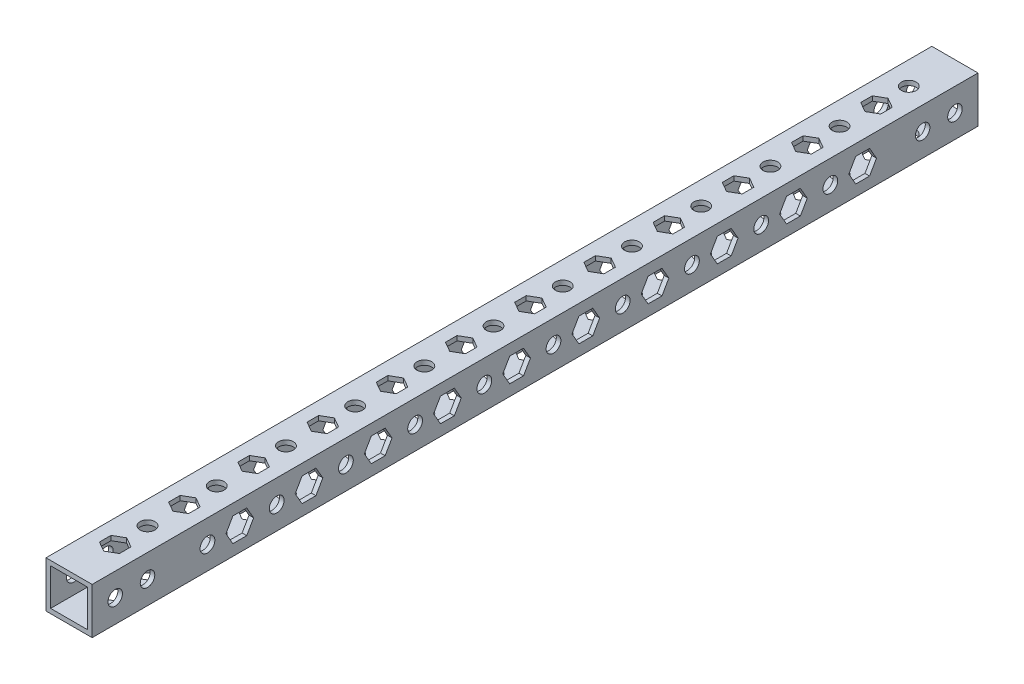
SolidWorks part; units mm, degrees
ref_plane "前视基准面" through (0, 0, 0) normal (0, 0, 1) x (1, 0, 0)
ref_plane "上视基准面" through (0, 0, 0) normal (0, 1, 0) x (1, 0, 0)
ref_plane "右视基准面" through (0, 0, 0) normal (1, 0, 0) x (0, 0, -1)
other "Configuration Table"
sketch "草图1" plane through (0, 0, 0) normal (0, 0, 1) x (1, 0, 0)
  line L1 (0, 0) -> (10, 0)
  line L2 (0, 0) -> (0, -10)
  line L3 (0, -10) -> (10, -10)
  line L4 (10, 0) -> (10, -10)
  dimension "D1" = 10
  dimension "D2" = 10
extrude "拉伸-薄壁1" add sketch "草图1" along normal blind 192 thin
sketch "草图2" plane through (10, 0, 0) normal (1, 0, 0) x (0, 0, -1)
  line L0 (-96, 0) -> (-96, -10) construction
  line L1 (-192, 0) -> (0, 0) construction
  line L2 (-192, -10) -> (0, -10) construction
  line L3 (0, -5) -> (-192, -5) construction
  line L4 (0, -10) -> (0, 0) construction
  line L5 (-192, -10) -> (-192, 0) construction
  line L6 (-143.5, -2.4019) -> (-146.5, -2.4019)
  line L7 (-157, -5) -> (-158.5, -2.4019)
  line L8 (-158.5, -2.4019) -> (-161.5, -2.4019)
  line L9 (-161.5, -2.4019) -> (-163, -5)
  line L10 (-163, -5) -> (-161.5, -7.5981)
  line L11 (-161.5, -7.5981) -> (-158.5, -7.5981)
  line L12 (-158.5, -7.5981) -> (-157, -5)
  line L13 (-142, -5) -> (-143.5, -2.4019)
  line L14 (-143.5, -7.5981) -> (-142, -5)
  line L15 (-146.5, -7.5981) -> (-143.5, -7.5981)
  line L16 (-148, -5) -> (-146.5, -7.5981)
  line L17 (-146.5, -2.4019) -> (-148, -5)
  line L18 (-128.5, -2.4019) -> (-131.5, -2.4019)
  line L19 (-127, -5) -> (-128.5, -2.4019)
  line L20 (-128.5, -7.5981) -> (-127, -5)
  line L21 (-131.5, -7.5981) -> (-128.5, -7.5981)
  line L22 (-133, -5) -> (-131.5, -7.5981)
  line L23 (-131.5, -2.4019) -> (-133, -5)
  line L24 (-113.5, -2.4019) -> (-116.5, -2.4019)
  line L25 (-112, -5) -> (-113.5, -2.4019)
  line L26 (-113.5, -7.5981) -> (-112, -5)
  line L27 (-116.5, -7.5981) -> (-113.5, -7.5981)
  line L28 (-118, -5) -> (-116.5, -7.5981)
  line L29 (-116.5, -2.4019) -> (-118, -5)
  line L30 (-98.5, -2.4019) -> (-101.5, -2.4019)
  line L31 (-97, -5) -> (-98.5, -2.4019)
  line L32 (-98.5, -7.5981) -> (-97, -5)
  line L33 (-101.5, -7.5981) -> (-98.5, -7.5981)
  line L34 (-103, -5) -> (-101.5, -7.5981)
  line L35 (-101.5, -2.4019) -> (-103, -5)
  line L36 (-83.5, -2.4019) -> (-86.5, -2.4019)
  line L37 (-82, -5) -> (-83.5, -2.4019)
  line L38 (-83.5, -7.5981) -> (-82, -5)
  line L39 (-86.5, -7.5981) -> (-83.5, -7.5981)
  line L40 (-88, -5) -> (-86.5, -7.5981)
  line L41 (-86.5, -2.4019) -> (-88, -5)
  line L42 (-68.5, -2.4019) -> (-71.5, -2.4019)
  line L43 (-67, -5) -> (-68.5, -2.4019)
  line L44 (-68.5, -7.5981) -> (-67, -5)
  line L45 (-71.5, -7.5981) -> (-68.5, -7.5981)
  line L46 (-73, -5) -> (-71.5, -7.5981)
  line L47 (-71.5, -2.4019) -> (-73, -5)
  line L48 (-53.5, -2.4019) -> (-56.5, -2.4019)
  line L49 (-52, -5) -> (-53.5, -2.4019)
  line L50 (-53.5, -7.5981) -> (-52, -5)
  line L51 (-56.5, -7.5981) -> (-53.5, -7.5981)
  line L52 (-58, -5) -> (-56.5, -7.5981)
  line L53 (-56.5, -2.4019) -> (-58, -5)
  line L54 (-38.5, -2.4019) -> (-41.5, -2.4019)
  line L55 (-37, -5) -> (-38.5, -2.4019)
  line L56 (-38.5, -7.5981) -> (-37, -5)
  line L57 (-41.5, -7.5981) -> (-38.5, -7.5981)
  line L58 (-43, -5) -> (-41.5, -7.5981)
  line L59 (-41.5, -2.4019) -> (-43, -5)
  line L60 (-23.5, -2.4019) -> (-26.5, -2.4019)
  line L61 (-22, -5) -> (-23.5, -2.4019)
  line L62 (-23.5, -7.5981) -> (-22, -5)
  line L63 (-26.5, -7.5981) -> (-23.5, -7.5981)
  line L64 (-28, -5) -> (-26.5, -7.5981)
  line L65 (-26.5, -2.4019) -> (-28, -5)
  circle A0 centre (-5, -5) radius 1.575
  circle A1 centre (-187, -5) radius 1.575
  circle A2 centre (-12, -5) radius 1.575
  circle A3 centre (-180, -5) radius 1.575
  circle A4 centre (-167, -5) radius 1.6
  circle A5 centre (-160, -5) radius 2.5981 construction
  circle A6 centre (-152, -5) radius 1.6
  circle A7 centre (-145, -5) radius 2.5981 construction
  circle A8 centre (-137, -5) radius 1.6
  circle A9 centre (-130, -5) radius 2.5981 construction
  circle A10 centre (-122, -5) radius 1.6
  circle A11 centre (-115, -5) radius 2.5981 construction
  circle A12 centre (-107, -5) radius 1.6
  circle A13 centre (-100, -5) radius 2.5981 construction
  circle A14 centre (-92, -5) radius 1.6
  circle A15 centre (-85, -5) radius 2.5981 construction
  circle A16 centre (-77, -5) radius 1.6
  circle A17 centre (-70, -5) radius 2.5981 construction
  circle A18 centre (-62, -5) radius 1.6
  circle A19 centre (-55, -5) radius 2.5981 construction
  circle A20 centre (-47, -5) radius 1.6
  circle A21 centre (-40, -5) radius 2.5981 construction
  circle A22 centre (-32, -5) radius 1.6
  circle A23 centre (-25, -5) radius 2.5981 construction
  dimension "D1" = 3.15
  dimension "D3" = 3.15
  dimension "D5" = 3.2
  dimension "D2" = 91
  dimension "D4" = 7
  dimension "D6" = 3
  dimension "D7" = 7
  dimension "D8" = 25
  dimension "D9" = 15
extrude "切除-拉伸1" cut sketch "草图2" against normal through all
sketch "草图3" plane through (0, 0, 0) normal (0, 1, 0) x (1, 0, 0)
  line L0 (5, 0) -> (5, -192) construction
  line L1 (10, 0) -> (0, 0) construction
  line L2 (10, -192) -> (0, -192) construction
  line L3 (7.1651, -30.75) -> (5, -29.5)
  line L4 (5, -14.5) -> (2.8349, -15.75)
  line L5 (2.8349, -15.75) -> (2.8349, -18.25)
  line L6 (2.8349, -18.25) -> (5, -19.5)
  line L7 (5, -19.5) -> (7.1651, -18.25)
  line L8 (7.1651, -18.25) -> (7.1651, -15.75)
  line L9 (7.1651, -15.75) -> (5, -14.5)
  line L10 (7.1651, -33.25) -> (7.1651, -30.75)
  line L11 (5, -34.5) -> (7.1651, -33.25)
  line L12 (2.8349, -30.75) -> (2.8349, -33.25)
  line L13 (5, -29.5) -> (2.8349, -30.75)
  line L14 (2.8349, -33.25) -> (5, -34.5)
  line L15 (7.1651, -45.75) -> (5, -44.5)
  line L16 (7.1651, -48.25) -> (7.1651, -45.75)
  line L17 (5, -49.5) -> (7.1651, -48.25)
  line L18 (2.8349, -45.75) -> (2.8349, -48.25)
  line L19 (5, -44.5) -> (2.8349, -45.75)
  line L20 (2.8349, -48.25) -> (5, -49.5)
  line L21 (7.1651, -60.75) -> (5, -59.5)
  line L22 (7.1651, -63.25) -> (7.1651, -60.75)
  line L23 (5, -64.5) -> (7.1651, -63.25)
  line L24 (2.8349, -60.75) -> (2.8349, -63.25)
  line L25 (5, -59.5) -> (2.8349, -60.75)
  line L26 (2.8349, -63.25) -> (5, -64.5)
  line L27 (7.1651, -75.75) -> (5, -74.5)
  line L28 (7.1651, -78.25) -> (7.1651, -75.75)
  line L29 (5, -79.5) -> (7.1651, -78.25)
  line L30 (2.8349, -75.75) -> (2.8349, -78.25)
  line L31 (5, -74.5) -> (2.8349, -75.75)
  line L32 (2.8349, -78.25) -> (5, -79.5)
  line L33 (7.1651, -90.75) -> (5, -89.5)
  line L34 (7.1651, -93.25) -> (7.1651, -90.75)
  line L35 (5, -94.5) -> (7.1651, -93.25)
  line L36 (2.8349, -90.75) -> (2.8349, -93.25)
  line L37 (5, -89.5) -> (2.8349, -90.75)
  line L38 (2.8349, -93.25) -> (5, -94.5)
  line L39 (7.1651, -105.75) -> (5, -104.5)
  line L40 (7.1651, -108.25) -> (7.1651, -105.75)
  line L41 (5, -109.5) -> (7.1651, -108.25)
  line L42 (2.8349, -105.75) -> (2.8349, -108.25)
  line L43 (5, -104.5) -> (2.8349, -105.75)
  line L44 (2.8349, -108.25) -> (5, -109.5)
  line L45 (7.1651, -120.75) -> (5, -119.5)
  line L46 (7.1651, -123.25) -> (7.1651, -120.75)
  line L47 (5, -124.5) -> (7.1651, -123.25)
  line L48 (2.8349, -120.75) -> (2.8349, -123.25)
  line L49 (5, -119.5) -> (2.8349, -120.75)
  line L50 (2.8349, -123.25) -> (5, -124.5)
  line L51 (7.1651, -135.75) -> (5, -134.5)
  line L52 (7.1651, -138.25) -> (7.1651, -135.75)
  line L53 (5, -139.5) -> (7.1651, -138.25)
  line L54 (2.8349, -135.75) -> (2.8349, -138.25)
  line L55 (5, -134.5) -> (2.8349, -135.75)
  line L56 (2.8349, -138.25) -> (5, -139.5)
  line L57 (7.1651, -150.75) -> (5, -149.5)
  line L58 (7.1651, -153.25) -> (7.1651, -150.75)
  line L59 (5, -154.5) -> (7.1651, -153.25)
  line L60 (2.8349, -150.75) -> (2.8349, -153.25)
  line L61 (5, -149.5) -> (2.8349, -150.75)
  line L62 (2.8349, -153.25) -> (5, -154.5)
  line L63 (7.1651, -165.75) -> (5, -164.5)
  line L64 (7.1651, -168.25) -> (7.1651, -165.75)
  line L65 (5, -169.5) -> (7.1651, -168.25)
  line L66 (2.8349, -165.75) -> (2.8349, -168.25)
  line L67 (5, -164.5) -> (2.8349, -165.75)
  line L68 (2.8349, -168.25) -> (5, -169.5)
  line L69 (7.1651, -180.75) -> (5, -179.5)
  line L70 (7.1651, -183.25) -> (7.1651, -180.75)
  line L71 (5, -184.5) -> (7.1651, -183.25)
  line L72 (2.8349, -180.75) -> (2.8349, -183.25)
  line L73 (5, -179.5) -> (2.8349, -180.75)
  line L74 (2.8349, -183.25) -> (5, -184.5)
  circle A1 centre (5, -10) radius 1.6
  circle A2 centre (5, -17) radius 2.1651 construction
  circle A3 centre (5, -25) radius 1.6
  circle A4 centre (5, -32) radius 2.1651 construction
  circle A5 centre (5, -40) radius 1.6
  circle A6 centre (5, -47) radius 2.1651 construction
  circle A7 centre (5, -55) radius 1.6
  circle A8 centre (5, -62) radius 2.1651 construction
  circle A9 centre (5, -70) radius 1.6
  circle A10 centre (5, -77) radius 2.1651 construction
  circle A11 centre (5, -85) radius 1.6
  circle A12 centre (5, -92) radius 2.1651 construction
  circle A13 centre (5, -100) radius 1.6
  circle A14 centre (5, -107) radius 2.1651 construction
  circle A15 centre (5, -115) radius 1.6
  circle A16 centre (5, -122) radius 2.1651 construction
  circle A17 centre (5, -130) radius 1.6
  circle A18 centre (5, -137) radius 2.1651 construction
  circle A19 centre (5, -145) radius 1.6
  circle A20 centre (5, -152) radius 2.1651 construction
  circle A21 centre (5, -160) radius 1.6
  circle A22 centre (5, -167) radius 2.1651 construction
  circle A23 centre (5, -175) radius 1.6
  circle A24 centre (5, -182) radius 2.1651 construction
  dimension "D1" = 3.2
  dimension "D2" = 10
  dimension "D3" = 2.5
  dimension "D4" = 7
  dimension "D5" = 15
extrude "切除-拉伸2" cut sketch "草图3" against normal through all
